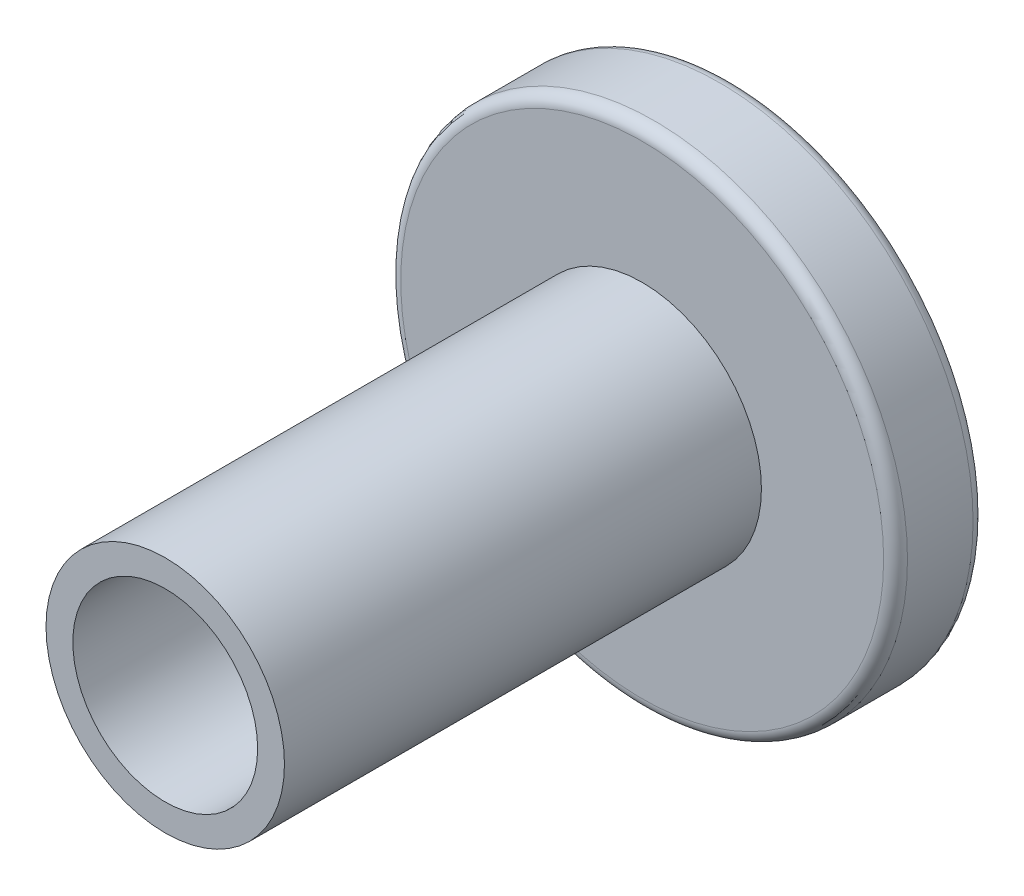
SolidWorks part; units mm, degrees
material "AISI 304"
ref_plane "前视基准面" through (0, 0, 0) normal (0, 0, 1) x (1, 0, 0)
ref_plane "上视基准面" through (0, 0, 0) normal (0, 1, 0) x (1, 0, 0)
ref_plane "右视基准面" through (0, 0, 0) normal (1, 0, 0) x (0, 0, -1)
other "Configuration Table"
sketch "草图1" plane through (0, 0, 0) normal (0, 0, 1) x (1, 0, 0)
  circle A0 centre (0, 0) radius 4.25
  dimension "D1" = 8.5
extrude "凸台-拉伸1" add sketch "草图1" along normal blind 1.5
sketch "草图2" plane through (0, 0, 1.5) normal (0, 0, 1) x (1, 0, 0)
  circle A0 centre (0, 0) radius 2
  circle A1 centre (0, 0) radius 1.55
  dimension "D1" = 4
  dimension "D2" = 3.1
extrude "凸台-拉伸2" add sketch "草图2" along normal blind 8
fillet "圆角1" radius 0.2 2 edges at (4.25, 0, 0) (4.25, 0, 1.5)
sketch "草图3" plane through (0, 0, 0) normal (0, 0, -1) x (-1, 0, 0)
  line L0 (0, 0) -> (1.4434, 0) construction
  line L1 (1.4434, 0) -> (0.7217, 1.25)
  line L2 (0.7217, 1.25) -> (-0.7217, 1.25)
  line L3 (-0.7217, 1.25) -> (-1.4434, 0)
  line L4 (-1.4434, 0) -> (-0.7217, -1.25)
  line L5 (-0.7217, -1.25) -> (0.7217, -1.25)
  line L6 (0.7217, -1.25) -> (1.4434, 0)
  circle A0 centre (0, 0) radius 1.25 construction
  dimension "D1" = 2.5
extrude "切除-拉伸1" cut sketch "草图3" against normal blind 1.5
